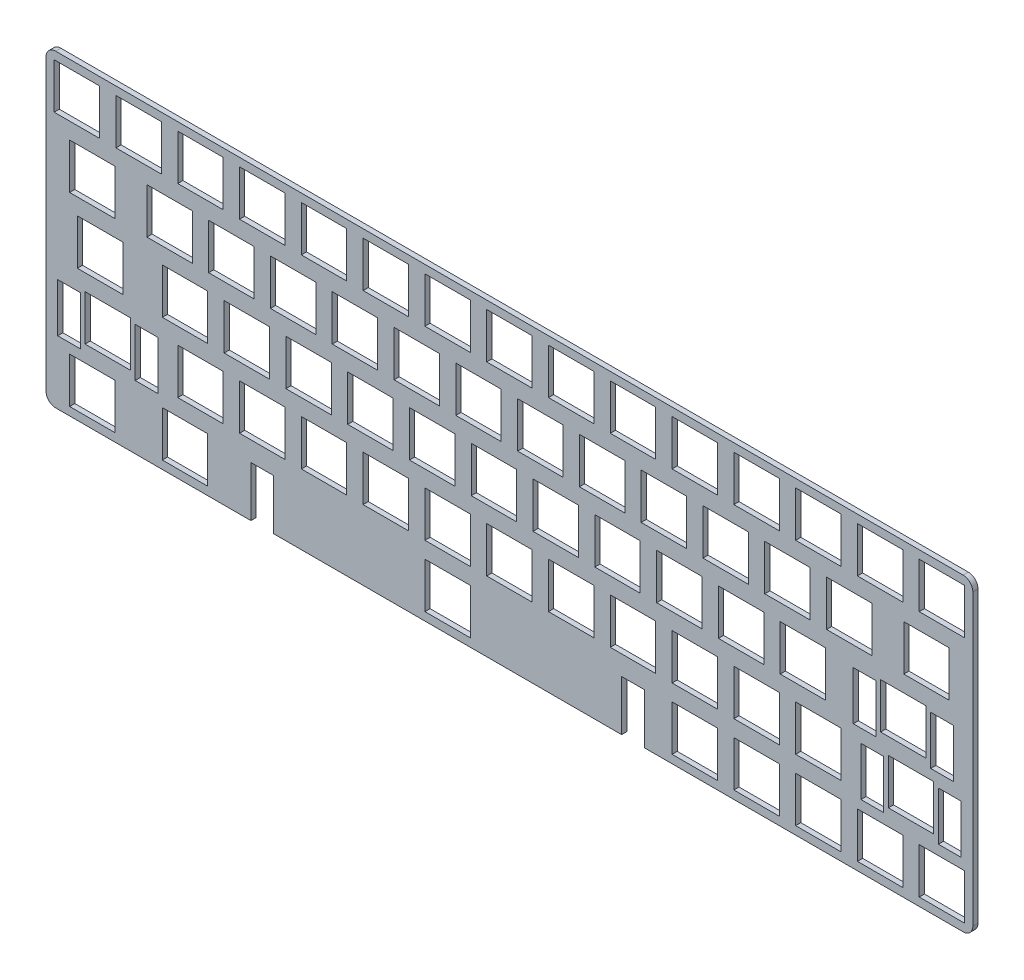
SolidWorks part; units mm, degrees
ref_plane "Front Plane" through (0, 0, 0) normal (0, 0, 1) x (1, 0, 0)
ref_plane "Top Plane" through (0, 0, 0) normal (0, 1, 0) x (1, 0, 0)
ref_plane "Right Plane" through (0, 0, 0) normal (1, 0, 0) x (0, 0, -1)
sketch "Model" plane through (0, 0, 0) normal (0, 0, 1) x (1, 0, 0)
  line L0 (2.525, -2.525) -> (16.525, -2.525)
  line L1 (2.525, -16.525) -> (16.525, -16.525)
  line L2 (2.525, -2.525) -> (2.525, -16.525)
  line L3 (16.525, -2.525) -> (16.525, -16.525)
  line L4 (21.575, -2.525) -> (35.575, -2.525)
  line L5 (21.575, -16.525) -> (35.575, -16.525)
  line L6 (21.575, -2.525) -> (21.575, -16.525)
  line L7 (35.575, -2.525) -> (35.575, -16.525)
  line L8 (40.625, -2.525) -> (54.625, -2.525)
  line L9 (40.625, -16.525) -> (54.625, -16.525)
  line L10 (40.625, -2.525) -> (40.625, -16.525)
  line L11 (54.625, -2.525) -> (54.625, -16.525)
  line L12 (59.675, -2.525) -> (73.675, -2.525)
  line L13 (59.675, -16.525) -> (73.675, -16.525)
  line L14 (59.675, -2.525) -> (59.675, -16.525)
  line L15 (73.675, -2.525) -> (73.675, -16.525)
  line L16 (78.725, -2.525) -> (92.725, -2.525)
  line L17 (78.725, -16.525) -> (92.725, -16.525)
  line L18 (78.725, -2.525) -> (78.725, -16.525)
  line L19 (92.725, -2.525) -> (92.725, -16.525)
  line L20 (97.775, -2.525) -> (111.775, -2.525)
  line L21 (97.775, -16.525) -> (111.775, -16.525)
  line L22 (97.775, -2.525) -> (97.775, -16.525)
  line L23 (111.775, -2.525) -> (111.775, -16.525)
  line L24 (116.825, -2.525) -> (130.825, -2.525)
  line L25 (116.825, -16.525) -> (130.825, -16.525)
  line L26 (116.825, -2.525) -> (116.825, -16.525)
  line L27 (130.825, -2.525) -> (130.825, -16.525)
  line L28 (135.875, -2.525) -> (149.875, -2.525)
  line L29 (135.875, -16.525) -> (149.875, -16.525)
  line L30 (135.875, -2.525) -> (135.875, -16.525)
  line L31 (149.875, -2.525) -> (149.875, -16.525)
  line L32 (154.925, -2.525) -> (168.925, -2.525)
  line L33 (154.925, -16.525) -> (168.925, -16.525)
  line L34 (154.925, -2.525) -> (154.925, -16.525)
  line L35 (168.925, -2.525) -> (168.925, -16.525)
  line L36 (173.975, -2.525) -> (187.975, -2.525)
  line L37 (173.975, -16.525) -> (187.975, -16.525)
  line L38 (173.975, -2.525) -> (173.975, -16.525)
  line L39 (187.975, -2.525) -> (187.975, -16.525)
  line L40 (193.025, -2.525) -> (207.025, -2.525)
  line L41 (193.025, -16.525) -> (207.025, -16.525)
  line L42 (193.025, -2.525) -> (193.025, -16.525)
  line L43 (207.025, -2.525) -> (207.025, -16.525)
  line L44 (212.075, -2.525) -> (226.075, -2.525)
  line L45 (212.075, -16.525) -> (226.075, -16.525)
  line L46 (212.075, -2.525) -> (212.075, -16.525)
  line L47 (226.075, -2.525) -> (226.075, -16.525)
  line L48 (231.125, -2.525) -> (245.125, -2.525)
  line L49 (231.125, -16.525) -> (245.125, -16.525)
  line L50 (231.125, -2.525) -> (231.125, -16.525)
  line L51 (245.125, -2.525) -> (245.125, -16.525)
  line L52 (250.175, -2.525) -> (264.175, -2.525)
  line L53 (250.175, -16.525) -> (264.175, -16.525)
  line L54 (250.175, -2.525) -> (250.175, -16.525)
  line L55 (264.175, -2.525) -> (264.175, -16.525)
  line L56 (269.225, -2.525) -> (283.225, -2.525)
  line L57 (269.225, -16.525) -> (283.225, -16.525)
  line L58 (269.225, -2.525) -> (269.225, -16.525)
  line L59 (283.225, -2.525) -> (283.225, -16.525)
  line L60 (7.2875, -21.575) -> (21.2875, -21.575)
  line L61 (7.2875, -35.575) -> (21.2875, -35.575)
  line L62 (7.2875, -21.575) -> (7.2875, -35.575)
  line L63 (21.2875, -21.575) -> (21.2875, -35.575)
  line L64 (31.1, -21.575) -> (45.1, -21.575)
  line L65 (31.1, -35.575) -> (45.1, -35.575)
  line L66 (31.1, -21.575) -> (31.1, -35.575)
  line L67 (45.1, -21.575) -> (45.1, -35.575)
  line L68 (50.15, -21.575) -> (64.15, -21.575)
  line L69 (50.15, -35.575) -> (64.15, -35.575)
  line L70 (50.15, -21.575) -> (50.15, -35.575)
  line L71 (64.15, -21.575) -> (64.15, -35.575)
  line L72 (69.2, -21.575) -> (83.2, -21.575)
  line L73 (69.2, -35.575) -> (83.2, -35.575)
  line L74 (69.2, -21.575) -> (69.2, -35.575)
  line L75 (83.2, -21.575) -> (83.2, -35.575)
  line L76 (88.25, -21.575) -> (102.25, -21.575)
  line L77 (88.25, -35.575) -> (102.25, -35.575)
  line L78 (88.25, -21.575) -> (88.25, -35.575)
  line L79 (102.25, -21.575) -> (102.25, -35.575)
  line L80 (107.3, -21.575) -> (121.3, -21.575)
  line L81 (107.3, -35.575) -> (121.3, -35.575)
  line L82 (107.3, -21.575) -> (107.3, -35.575)
  line L83 (121.3, -21.575) -> (121.3, -35.575)
  line L84 (126.35, -21.575) -> (140.35, -21.575)
  line L85 (126.35, -35.575) -> (140.35, -35.575)
  line L86 (126.35, -21.575) -> (126.35, -35.575)
  line L87 (140.35, -21.575) -> (140.35, -35.575)
  line L88 (145.4, -21.575) -> (159.4, -21.575)
  line L89 (145.4, -35.575) -> (159.4, -35.575)
  line L90 (145.4, -21.575) -> (145.4, -35.575)
  line L91 (159.4, -21.575) -> (159.4, -35.575)
  line L92 (164.45, -21.575) -> (178.45, -21.575)
  line L93 (164.45, -35.575) -> (178.45, -35.575)
  line L94 (164.45, -21.575) -> (164.45, -35.575)
  line L95 (178.45, -21.575) -> (178.45, -35.575)
  line L96 (183.5, -21.575) -> (197.5, -21.575)
  line L97 (183.5, -35.575) -> (197.5, -35.575)
  line L98 (183.5, -21.575) -> (183.5, -35.575)
  line L99 (197.5, -21.575) -> (197.5, -35.575)
  line L100 (202.55, -21.575) -> (216.55, -21.575)
  line L101 (202.55, -35.575) -> (216.55, -35.575)
  line L102 (202.55, -21.575) -> (202.55, -35.575)
  line L103 (216.55, -21.575) -> (216.55, -35.575)
  line L104 (221.6, -21.575) -> (235.6, -21.575)
  line L105 (221.6, -35.575) -> (235.6, -35.575)
  line L106 (221.6, -21.575) -> (221.6, -35.575)
  line L107 (235.6, -21.575) -> (235.6, -35.575)
  line L108 (240.65, -21.575) -> (254.65, -21.575)
  line L109 (240.65, -35.575) -> (254.65, -35.575)
  line L110 (240.65, -21.575) -> (240.65, -35.575)
  line L111 (254.65, -21.575) -> (254.65, -35.575)
  line L112 (264.4625, -21.575) -> (278.4625, -21.575)
  line L113 (264.4625, -35.575) -> (278.4625, -35.575)
  line L114 (264.4625, -21.575) -> (264.4625, -35.575)
  line L115 (278.4625, -21.575) -> (278.4625, -35.575)
  line L116 (9.6688, -40.625) -> (23.6687, -40.625)
  line L117 (9.6688, -54.625) -> (23.6687, -54.625)
  line L118 (9.6688, -40.625) -> (9.6688, -54.625)
  line L119 (23.6687, -40.625) -> (23.6687, -54.625)
  line L120 (35.8625, -40.625) -> (49.8625, -40.625)
  line L121 (35.8625, -54.625) -> (49.8625, -54.625)
  line L122 (35.8625, -40.625) -> (35.8625, -54.625)
  line L123 (49.8625, -40.625) -> (49.8625, -54.625)
  line L124 (54.9125, -40.625) -> (68.9125, -40.625)
  line L125 (54.9125, -54.625) -> (68.9125, -54.625)
  line L126 (54.9125, -40.625) -> (54.9125, -54.625)
  line L127 (68.9125, -40.625) -> (68.9125, -54.625)
  line L128 (73.9625, -40.625) -> (87.9625, -40.625)
  line L129 (73.9625, -54.625) -> (87.9625, -54.625)
  line L130 (73.9625, -40.625) -> (73.9625, -54.625)
  line L131 (87.9625, -40.625) -> (87.9625, -54.625)
  line L132 (93.0125, -40.625) -> (107.0125, -40.625)
  line L133 (93.0125, -54.625) -> (107.0125, -54.625)
  line L134 (93.0125, -40.625) -> (93.0125, -54.625)
  line L135 (107.0125, -40.625) -> (107.0125, -54.625)
  line L136 (112.0625, -40.625) -> (126.0625, -40.625)
  line L137 (112.0625, -54.625) -> (126.0625, -54.625)
  line L138 (112.0625, -40.625) -> (112.0625, -54.625)
  line L139 (126.0625, -40.625) -> (126.0625, -54.625)
  line L140 (131.1125, -40.625) -> (145.1125, -40.625)
  line L141 (131.1125, -54.625) -> (145.1125, -54.625)
  line L142 (131.1125, -40.625) -> (131.1125, -54.625)
  line L143 (145.1125, -40.625) -> (145.1125, -54.625)
  line L144 (150.1625, -40.625) -> (164.1625, -40.625)
  line L145 (150.1625, -54.625) -> (164.1625, -54.625)
  line L146 (150.1625, -40.625) -> (150.1625, -54.625)
  line L147 (164.1625, -40.625) -> (164.1625, -54.625)
  line L148 (169.2125, -40.625) -> (183.2125, -40.625)
  line L149 (169.2125, -54.625) -> (183.2125, -54.625)
  line L150 (169.2125, -40.625) -> (169.2125, -54.625)
  line L151 (183.2125, -40.625) -> (183.2125, -54.625)
  line L152 (188.2625, -40.625) -> (202.2625, -40.625)
  line L153 (188.2625, -54.625) -> (202.2625, -54.625)
  line L154 (188.2625, -40.625) -> (188.2625, -54.625)
  line L155 (202.2625, -40.625) -> (202.2625, -54.625)
  line L156 (207.3125, -40.625) -> (221.3125, -40.625)
  line L157 (207.3125, -54.625) -> (221.3125, -54.625)
  line L158 (207.3125, -40.625) -> (207.3125, -54.625)
  line L159 (221.3125, -40.625) -> (221.3125, -54.625)
  line L160 (226.3625, -40.625) -> (240.3625, -40.625)
  line L161 (226.3625, -54.625) -> (240.3625, -54.625)
  line L162 (226.3625, -40.625) -> (226.3625, -54.625)
  line L163 (240.3625, -40.625) -> (240.3625, -54.625)
  line L164 (257.3188, -40.625) -> (271.3188, -40.625)
  line L165 (257.3188, -54.625) -> (271.3188, -54.625)
  line L166 (257.3188, -40.625) -> (257.3188, -54.625)
  line L167 (271.3188, -40.625) -> (271.3188, -54.625)
  line L168 (272.7568, -41.625) -> (279.7568, -41.625)
  line L169 (272.7568, -56.625) -> (279.7568, -56.625)
  line L170 (272.7568, -41.625) -> (272.7568, -56.625)
  line L171 (279.7568, -41.625) -> (279.7568, -56.625)
  line L172 (248.8808, -41.625) -> (255.8807, -41.625)
  line L173 (248.8808, -56.625) -> (255.8807, -56.625)
  line L174 (248.8808, -41.625) -> (248.8808, -56.625)
  line L175 (255.8807, -41.625) -> (255.8807, -56.625)
  line L176 (12.05, -59.675) -> (26.05, -59.675)
  line L177 (12.05, -73.675) -> (26.05, -73.675)
  line L178 (12.05, -59.675) -> (12.05, -73.675)
  line L179 (26.05, -59.675) -> (26.05, -73.675)
  line L180 (27.488, -60.675) -> (34.488, -60.675)
  line L181 (27.488, -75.675) -> (34.488, -75.675)
  line L182 (27.488, -60.675) -> (27.488, -75.675)
  line L183 (34.488, -60.675) -> (34.488, -75.675)
  line L184 (3.612, -60.675) -> (10.612, -60.675)
  line L185 (3.612, -75.675) -> (10.612, -75.675)
  line L186 (3.612, -60.675) -> (3.612, -75.675)
  line L187 (10.612, -60.675) -> (10.612, -75.675)
  line L188 (40.625, -59.675) -> (54.625, -59.675)
  line L189 (40.625, -73.675) -> (54.625, -73.675)
  line L190 (40.625, -59.675) -> (40.625, -73.675)
  line L191 (54.625, -59.675) -> (54.625, -73.675)
  line L192 (59.675, -59.675) -> (73.675, -59.675)
  line L193 (59.675, -73.675) -> (73.675, -73.675)
  line L194 (59.675, -59.675) -> (59.675, -73.675)
  line L195 (73.675, -59.675) -> (73.675, -73.675)
  line L196 (78.725, -59.675) -> (92.725, -59.675)
  line L197 (78.725, -73.675) -> (92.725, -73.675)
  line L198 (78.725, -59.675) -> (78.725, -73.675)
  line L199 (92.725, -59.675) -> (92.725, -73.675)
  line L200 (97.775, -59.675) -> (111.775, -59.675)
  line L201 (97.775, -73.675) -> (111.775, -73.675)
  line L202 (97.775, -59.675) -> (97.775, -73.675)
  line L203 (111.775, -59.675) -> (111.775, -73.675)
  line L204 (116.825, -59.675) -> (130.825, -59.675)
  line L205 (116.825, -73.675) -> (130.825, -73.675)
  line L206 (116.825, -59.675) -> (116.825, -73.675)
  line L207 (130.825, -59.675) -> (130.825, -73.675)
  line L208 (135.875, -59.675) -> (149.875, -59.675)
  line L209 (135.875, -73.675) -> (149.875, -73.675)
  line L210 (135.875, -59.675) -> (135.875, -73.675)
  line L211 (149.875, -59.675) -> (149.875, -73.675)
  line L212 (154.925, -59.675) -> (168.925, -59.675)
  line L213 (154.925, -73.675) -> (168.925, -73.675)
  line L214 (154.925, -59.675) -> (154.925, -73.675)
  line L215 (168.925, -59.675) -> (168.925, -73.675)
  line L216 (173.975, -59.675) -> (187.975, -59.675)
  line L217 (173.975, -73.675) -> (187.975, -73.675)
  line L218 (173.975, -59.675) -> (173.975, -73.675)
  line L219 (187.975, -59.675) -> (187.975, -73.675)
  line L220 (193.025, -59.675) -> (207.025, -59.675)
  line L221 (193.025, -73.675) -> (207.025, -73.675)
  line L222 (193.025, -59.675) -> (193.025, -73.675)
  line L223 (207.025, -59.675) -> (207.025, -73.675)
  line L224 (212.075, -59.675) -> (226.075, -59.675)
  line L225 (212.075, -73.675) -> (226.075, -73.675)
  line L226 (212.075, -59.675) -> (212.075, -73.675)
  line L227 (226.075, -59.675) -> (226.075, -73.675)
  line L228 (231.125, -59.675) -> (245.125, -59.675)
  line L229 (231.125, -73.675) -> (245.125, -73.675)
  line L230 (231.125, -59.675) -> (231.125, -73.675)
  line L231 (245.125, -59.675) -> (245.125, -73.675)
  line L232 (259.7, -59.675) -> (273.7, -59.675)
  line L233 (259.7, -73.675) -> (273.7, -73.675)
  line L234 (259.7, -59.675) -> (259.7, -73.675)
  line L235 (273.7, -59.675) -> (273.7, -73.675)
  line L236 (275.138, -60.675) -> (282.138, -60.675)
  line L237 (275.138, -75.675) -> (282.138, -75.675)
  line L238 (275.138, -60.675) -> (275.138, -75.675)
  line L239 (282.138, -60.675) -> (282.138, -75.675)
  line L240 (251.262, -60.675) -> (258.262, -60.675)
  line L241 (251.262, -75.675) -> (258.262, -75.675)
  line L242 (251.262, -60.675) -> (251.262, -75.675)
  line L243 (258.262, -60.675) -> (258.262, -75.675)
  line L244 (7.2875, -78.725) -> (21.2875, -78.725)
  line L245 (7.2875, -92.725) -> (21.2875, -92.725)
  line L246 (7.2875, -78.725) -> (7.2875, -92.725)
  line L247 (21.2875, -78.725) -> (21.2875, -92.725)
  line L248 (35.8625, -78.725) -> (49.8625, -78.725)
  line L249 (35.8625, -92.725) -> (49.8625, -92.725)
  line L250 (35.8625, -78.725) -> (35.8625, -92.725)
  line L251 (49.8625, -78.725) -> (49.8625, -92.725)
  line L252 (116.825, -78.725) -> (130.825, -78.725)
  line L253 (116.825, -92.725) -> (130.825, -92.725)
  line L254 (116.825, -78.725) -> (116.825, -92.725)
  line L255 (130.825, -78.725) -> (130.825, -92.725)
  line L256 (177.475, -79.725) -> (184.475, -79.725)
  line L258 (177.475, -79.725) -> (177.475, -94.725)
  line L259 (184.475, -79.725) -> (184.475, -94.725)
  line L260 (63.175, -79.725) -> (70.175, -79.725)
  line L261 (177.475, -94.725) -> (177.475, -95.25)
  line L262 (63.175, -79.725) -> (63.175, -94.725)
  line L263 (70.175, -79.725) -> (70.175, -94.725)
  line L264 (193.025, -78.725) -> (207.025, -78.725)
  line L265 (193.025, -92.725) -> (207.025, -92.725)
  line L266 (193.025, -78.725) -> (193.025, -92.725)
  line L267 (207.025, -78.725) -> (207.025, -92.725)
  line L268 (212.075, -78.725) -> (226.075, -78.725)
  line L269 (212.075, -92.725) -> (226.075, -92.725)
  line L270 (212.075, -78.725) -> (212.075, -92.725)
  line L271 (226.075, -78.725) -> (226.075, -92.725)
  line L272 (231.125, -78.725) -> (245.125, -78.725)
  line L273 (231.125, -92.725) -> (245.125, -92.725)
  line L274 (231.125, -78.725) -> (231.125, -92.725)
  line L275 (245.125, -78.725) -> (245.125, -92.725)
  line L276 (250.175, -78.725) -> (264.175, -78.725)
  line L277 (250.175, -92.725) -> (264.175, -92.725)
  line L278 (250.175, -78.725) -> (250.175, -92.725)
  line L279 (264.175, -78.725) -> (264.175, -92.725)
  line L280 (269.225, -78.725) -> (283.225, -78.725)
  line L281 (269.225, -92.725) -> (283.225, -92.725)
  line L282 (269.225, -78.725) -> (269.225, -92.725)
  line L283 (283.225, -78.725) -> (283.225, -92.725)
  line L284 (3, 0) -> (282.75, 0)
  line L285 (3, -95.25) -> (63.175, -95.25)
  line L286 (0, -3) -> (0, -92.25)
  line L287 (285.75, -3) -> (285.75, -92.25)
  line L288 (63.175, -94.725) -> (63.175, -95.25)
  line L289 (70.175, -94.725) -> (70.175, -95.25)
  line L290 (70.175, -95.25) -> (177.475, -95.25)
  line L291 (184.475, -94.725) -> (184.475, -95.25)
  line L292 (184.475, -95.25) -> (282.75, -95.25)
  arc A0 (285.75, -3) -> (282.75, 0) centre (282.75, -3) ccw
  arc A1 (285.75, -92.25) -> (282.75, -95.25) centre (282.75, -92.25) cw
  arc A2 (3, -95.25) -> (0, -92.25) centre (3, -92.25) cw
  arc A3 (0, -3) -> (3, 0) centre (3, -3) cw
  dimension "D1" = 3
extrude "Boss-Extrude1" add sketch "Model" along normal blind 1.6
